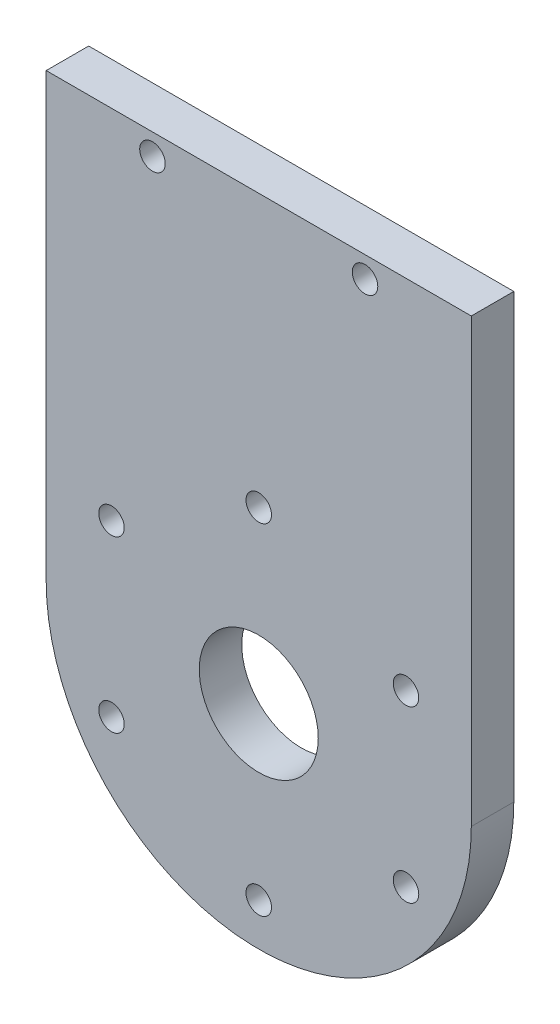
SolidWorks part; units mm, degrees
ref_plane "Plan de face" through (0, 0, 0) normal (0, 0, 1) x (1, 0, 0)
ref_plane "Plan de dessus" through (0, 0, 0) normal (0, 1, 0) x (1, 0, 0)
ref_plane "Plan de droite" through (0, 0, 0) normal (1, 0, 0) x (0, 0, -1)
sketch "Esquisse1" plane through (0, 0, 0) normal (0, 0, 1) x (1, 0, 0)
  line L0 (-50, 52) -> (50, 52)
  line L1 (-50, 52) -> (-50, -48.5481)
  line L2 (50, 52) -> (50, -48.5481)
  line L3 (-50, -48.5481) -> (50, -48.5481)
  circle A1 centre (0, 0) radius 7
  dimension "D1" = 52
extrude "Boss.-Extru.1" add sketch "Esquisse1" along normal blind 5
sketch "Esquisse2" plane through (0, 0, 5) normal (0, 0, 1) x (1, 0, 0)
  line L0 (-25, 0) -> (25, 0)
  line L1 (-25, 0) -> (-25, 55)
  line L2 (25, 0) -> (25, 55)
  line L3 (-25, 55) -> (25, 55)
  line L4 (-50, 52) -> (50, 52) construction
  circle A0 centre (0, 20) radius 1.5
  circle A1 centre (17.3205, 10) radius 1.5
  circle A2 centre (17.3205, -10) radius 1.5
  circle A3 centre (0, -20) radius 1.5
  circle A4 centre (-17.3205, -10) radius 1.5
  circle A5 centre (-17.3205, 10) radius 1.5
  circle A6 centre (0, 0) radius 25
  circle A8 centre (-12.5, 49.5) radius 1.5
  circle A9 centre (12.5, 49.5) radius 1.5
  point P4 (0, 0)
  point P12 (0, 0)
  point P33 (0, 0)
  dimension "D1" = 20
  dimension "D3" = 55
  dimension "D4" = 12.5
  dimension "D5" = 12.5
  dimension "D6" = 2.5
  dimension "D7" = 2.5
  dimension "D2" = 6
extrude "Enlèv. mat.-Extru.1" cut sketch "Esquisse2" against normal through all
